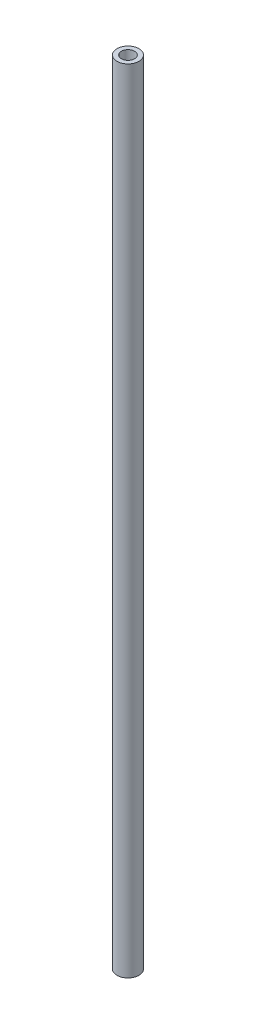
SolidWorks part; units mm, degrees
material "AISI Type 316L stainless steel"
ref_plane "Front" through (0, 0, 0) normal (0, 0, 1) x (1, 0, 0)
ref_plane "Top" through (0, 0, 0) normal (0, 1, 0) x (1, 0, 0)
ref_plane "Right" through (0, 0, 0) normal (1, 0, 0) x (0, 0, -1)
sketch "Sketch1" plane through (0, 0, 0) normal (0, 1, 0) x (1, 0, 0)
  circle A0 centre (0, 0) radius 12.5
  circle A1 centre (0, 0) radius 7.5
  dimension "D1" = 25
  dimension "D2" = 15
extrude "Boss-Extrude1" add sketch "Sketch1" along normal blind 900 contours A0 A1
